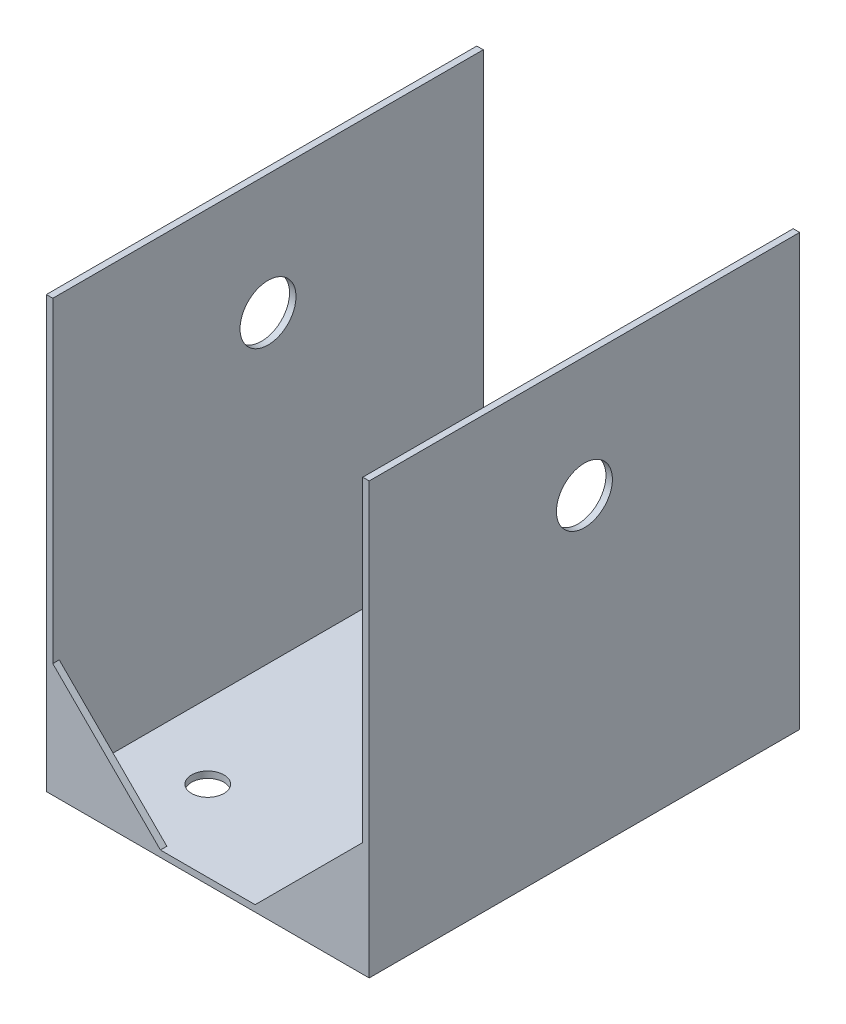
SolidWorks part; units mm, degrees
ref_plane "Front Plane" through (0, 0, 0) normal (0, 0, 1) x (1, 0, 0)
ref_plane "Top Plane" through (0, 0, 0) normal (0, 1, 0) x (1, 0, 0)
ref_plane "Right Plane" through (0, 0, 0) normal (1, 0, 0) x (0, 0, -1)
sketch "Sketch1" plane through (0, 0, 0) normal (0, 0, 1) x (1, 0, 0)
  line L0 (0, 0) -> (38.1, 0)
  line L1 (0, 0) -> (0, 50.8)
  line L2 (38.1, 0) -> (38.1, 50.8)
  line L3 (37.338, 0.762) -> (37.338, 50.8)
  line L4 (0.762, 0.762) -> (37.338, 0.762)
  line L5 (0.762, 0.762) -> (0.762, 50.8)
  line L6 (0, 50.8) -> (0.762, 50.8)
  line L7 (37.338, 50.8) -> (38.1, 50.8)
  dimension "D1" = 50.8
  dimension "D2" = 50.8
  dimension "D4" = 38.1
  dimension "D3" = 0.762
extrude "Boss-Extrude1" add sketch "Sketch1" along normal blind 50.8
sketch "Sketch2" plane through (0, 0, 50.8) normal (0, 0, 1) x (1, 0, 0)
  line L0 (0.762, 0.762) -> (13.462, 0.762)
  line L1 (37.338, 0.762) -> (0.762, 0.762) construction
  line L2 (13.462, 0.762) -> (0.762, 13.462)
  line L3 (0.762, 0.762) -> (0.762, 50.8) construction
  line L4 (0.762, 13.462) -> (0.762, 0.762)
  line L5 (19.05, 0.762) -> (19.05, 52.4839) construction
  line L6 (37.338, 0.762) -> (24.638, 0.762)
  line L7 (37.338, 13.462) -> (37.338, 0.762)
  line L8 (24.638, 0.762) -> (37.338, 13.462)
  dimension "D1" = 12.7
  dimension "D2" = 12.7
extrude "Boss-Extrude2" add sketch "Sketch2" against normal blind 0.762
sketch "Sketch3" plane through (0, 0, 0) normal (0, 0, -1) x (-1, 0, 0)
  line L0 (-37.338, 13.462) -> (-37.338, 0.762)
  line L1 (-37.338, 0.762) -> (-24.638, 0.762)
  line L2 (-24.638, 0.762) -> (-37.338, 13.462)
  line L3 (-19.05, 0.762) -> (-19.05, 46.4076) construction
  line L4 (-37.338, 0.762) -> (-0.762, 0.762) construction
  line L5 (-0.762, 0.762) -> (-13.462, 0.762)
  line L6 (-0.762, 13.462) -> (-0.762, 0.762)
  line L7 (-13.462, 0.762) -> (-0.762, 13.462)
extrude "Boss-Extrude3" add sketch "Sketch3" against normal blind 0.762
sketch "Sketch4" plane through (0, 0, 0) normal (-1, 0, 0) x (0, 0, 1)
  line L0 (25.4, 50.8) -> (25.4, 0) construction
  line L1 (50.8, 50.8) -> (0, 50.8) construction
  line L2 (50.8, 0) -> (0, 0) construction
  circle A0 centre (25.4, 36.6243) radius 3.302
extrude "Cut-Extrude1" cut sketch "Sketch4" against normal through all
sketch "Sketch5" plane through (0, 0.762, 0) normal (0, 1, 0) x (1, 0, 0)
  line L0 (0.762, 0) -> (13.462, 0) construction
  line L1 (0, -50.8) -> (0, 0) construction
  line L2 (19.05, 0) -> (19.05, -50.8) construction
  line L3 (24.638, 0) -> (13.462, 0) construction
  line L4 (24.638, -50.8) -> (13.462, -50.8) construction
  line L5 (0, -25.4) -> (38.1, -25.4) construction
  line L6 (38.1, -50.8) -> (38.1, 0) construction
  circle A0 centre (9.525, -9.525) radius 1.905
  circle A1 centre (9.525, -41.275) radius 1.905
  circle A2 centre (28.575, -41.275) radius 1.905
  circle A3 centre (28.575, -9.525) radius 1.905
  dimension "D1" = 9.525
  dimension "D2" = 9.525
extrude "Cut-Extrude2" cut sketch "Sketch5" against normal through all
